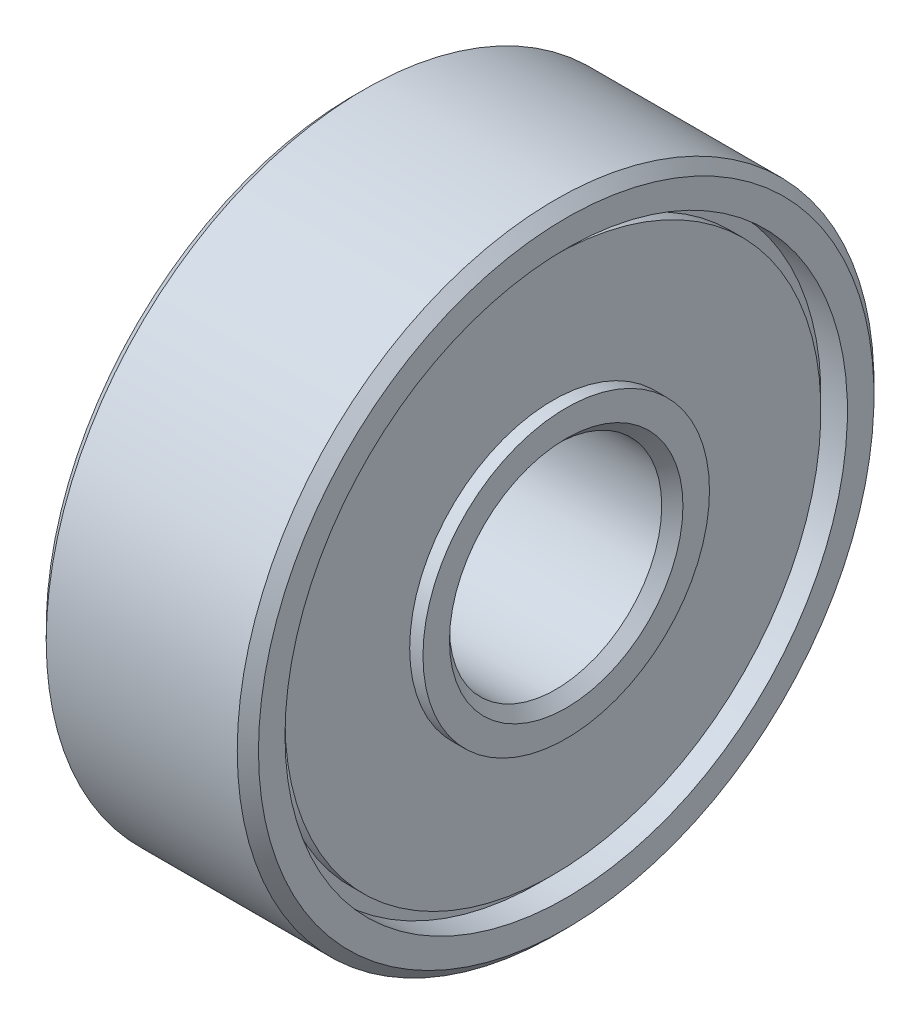
SolidWorks part; units mm, degrees
ref_plane "前视基准面" through (0, 0, 0) normal (0, 0, 1) x (1, 0, 0)
ref_plane "上视基准面" through (0, 0, 0) normal (0, 1, 0) x (1, 0, 0)
ref_plane "右视基准面" through (0, 0, 0) normal (1, 0, 0) x (0, 0, -1)
other "Configuration Table"
sketch "草图1" plane through (0, 0, 0) normal (0, 0, 1) x (1, 0, 0)
  line L0 (-3.901, 0) -> (3.7973, 0) construction
  line L1 (0, 7.17) -> (0, -5.7744) construction
  line L2 (-2, 2) -> (2, 2)
  line L3 (2, 2) -> (2, 2.7)
  line L4 (2, 2.7) -> (1.75, 2.7)
  line L5 (1.75, 2.7) -> (1.75, 5.05)
  line L6 (1.75, 5.05) -> (1.5, 5.05)
  line L7 (1.5, 5.05) -> (1.5, 5.3)
  line L8 (1.5, 5.3) -> (2, 5.3)
  line L9 (2, 5.3) -> (2, 6)
  line L10 (2, 6) -> (-2, 6)
  line L11 (-2, 5.3) -> (-2, 6)
  line L12 (-1.5, 5.3) -> (-2, 5.3)
  line L13 (-1.5, 5.05) -> (-1.5, 5.3)
  line L14 (-1.75, 5.05) -> (-1.5, 5.05)
  line L15 (-1.75, 2.7) -> (-1.75, 5.05)
  line L16 (-2, 2.7) -> (-1.75, 2.7)
  line L17 (-2, 2) -> (-2, 2.7)
  point P6 (-2, 2.35)
  point P16 (0, 6)
  point P23 (0, 2)
  dimension "D1" = 2
  dimension "D2" = 0.7
  dimension "D3" = 6
  dimension "D4" = 0.7
  dimension "D5" = 0.25
  dimension "D6" = 4
  dimension "D7" = 0.25
  dimension "D8" = 0.5
revolve "旋转1" add sketch "草图1" angle 360 about L0
chamfer "倒角1" distance 0.2 angle 45 4 edges at (2, 0, 6) (-2, 0, 6) (-2, 0, 2) (2, 0, 2)
